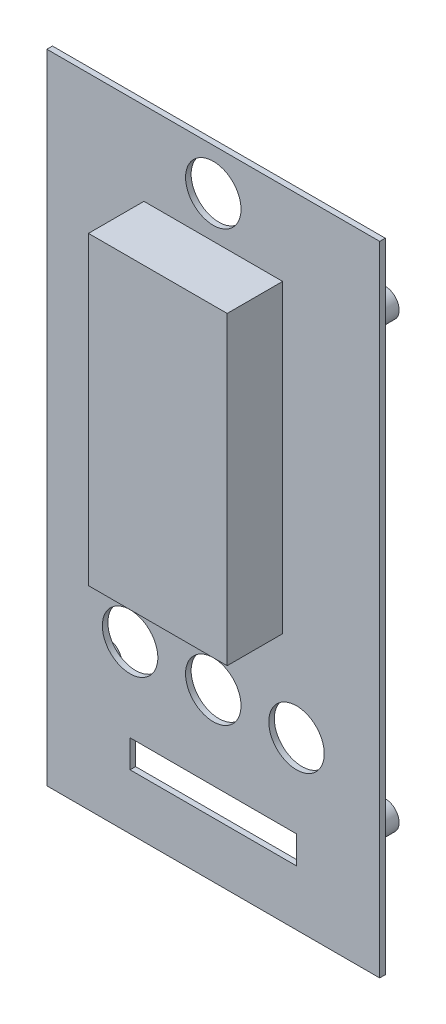
SolidWorks part; units mm, degrees
ref_plane "Front Plane" through (0, 0, 0) normal (0, 0, 1) x (1, 0, 0)
ref_plane "Top Plane" through (0, 0, 0) normal (0, 1, 0) x (1, 0, 0)
ref_plane "Right Plane" through (0, 0, 0) normal (1, 0, 0) x (0, 0, -1)
sketch "Sketch1" plane through (0, 0, -65) normal (0, 0, 1) x (1, 0, 0)
  line L0 (-25, 110) -> (-25, 30) construction
  line L1 (-25, 30) -> (25, 30) construction
  line L2 (25, 30) -> (25, 110) construction
  line L3 (25, 110) -> (-25, 110) construction
  line L4 (-37.5278, 70) -> (-25, 70) construction
  line L5 (-37.5278, 130) -> (-37.5278, 10) construction
  line L6 (37.5278, 70) -> (25, 70) construction
  line L7 (37.5278, 130) -> (37.5278, 10) construction
  line L8 (0, 130) -> (0, 110) construction
  line L9 (-43.3013, 130) -> (43.3013, 130) construction
  line L10 (0, 30) -> (0, 10) construction
  circle A0 centre (-25, 110) radius 2.5
  circle A1 centre (25, 110) radius 2.5
  circle A2 centre (25, 30) radius 2.5
  circle A3 centre (-25, 30) radius 2.5
  dimension "D2" = 5
  dimension "D1" = 80
  dimension "D3" = 50
extrude "Posts" add sketch "Sketch1" along normal blind 5
sketch "Sketch2" plane through (0, 0, -60) normal (0, 0, 1) x (1, 0, 0)
  line L0 (0, 125) -> (0, 10) construction
  line L2 (-30, 67.5) -> (-37.5278, 67.5) construction
  line L3 (-37.5278, 130) -> (-37.5278, 10) construction
  line L4 (30, 65.8545) -> (37.5278, 65.8545) construction
  line L5 (37.5278, 130) -> (37.5278, 10) construction
  line L14 (-30, 125) -> (-30, 10)
  line L15 (30, 125) -> (-30, 125)
  line L16 (30, 125) -> (30, 10)
  line L17 (30, 10) -> (-30, 10)
  dimension "D1" = 10
  dimension "D2" = 115
  dimension "D3" = 30
extrude "Electronics Circuit Board" add sketch "Sketch2" along normal blind 1
sketch "Sketch3" plane through (0, 0, -60) normal (0, 0, -1) x (-1, 0, 0)
  line L0 (-30, 40) -> (30, 40) construction
  line L2 (-30, 10) -> (-30, 125) construction
  line L6 (30, 10) -> (-30, 10) construction
  line L7 (-30, 125) -> (30, 125) construction
  line L8 (-15, 20) -> (15, 20)
  line L9 (-15, 20) -> (-15, 25)
  line L10 (-15, 25) -> (15, 25)
  line L11 (15, 20) -> (15, 25)
  line L12 (-15, 20) -> (15, 25) construction
  line L13 (-15, 25) -> (15, 20) construction
  line L14 (0, 40) -> (0, 130) construction
  circle A0 centre (0, 40) radius 5
  circle A1 centre (-15, 40) radius 5
  circle A2 centre (15, 40) radius 5
  circle A3 centre (0, 117.5) radius 5
  point P14 (0, 22.5)
  point P25 (0, 125)
  dimension "D2" = 10
  dimension "D1" = 30
  dimension "D3" = 15
  dimension "D4" = 15
  dimension "D5" = 7.5
extrude "Motor Leads" cut sketch "Sketch3" against normal through all
sketch "Sketch4" plane through (0, 0, -59) normal (0, 0, 1) x (1, 0, 0)
  line L0 (-12.5, 82.5) -> (-30, 82.5) construction
  line L1 (-12.5, 110) -> (12.5, 110)
  line L2 (-12.5, 110) -> (-12.5, 55)
  line L3 (-12.5, 55) -> (12.5, 55)
  line L4 (12.5, 110) -> (12.5, 55)
  line L5 (-30, 125) -> (-30, 10) construction
  line L6 (12.5, 82.5) -> (30, 82.5) construction
  line L7 (30, 10) -> (30, 125) construction
  line L8 (30, 125) -> (-30, 125) construction
  dimension "D1" = 55
  dimension "D2" = 25
  dimension "D3" = 15
extrude "ESC" add sketch "Sketch4" along normal blind 10
